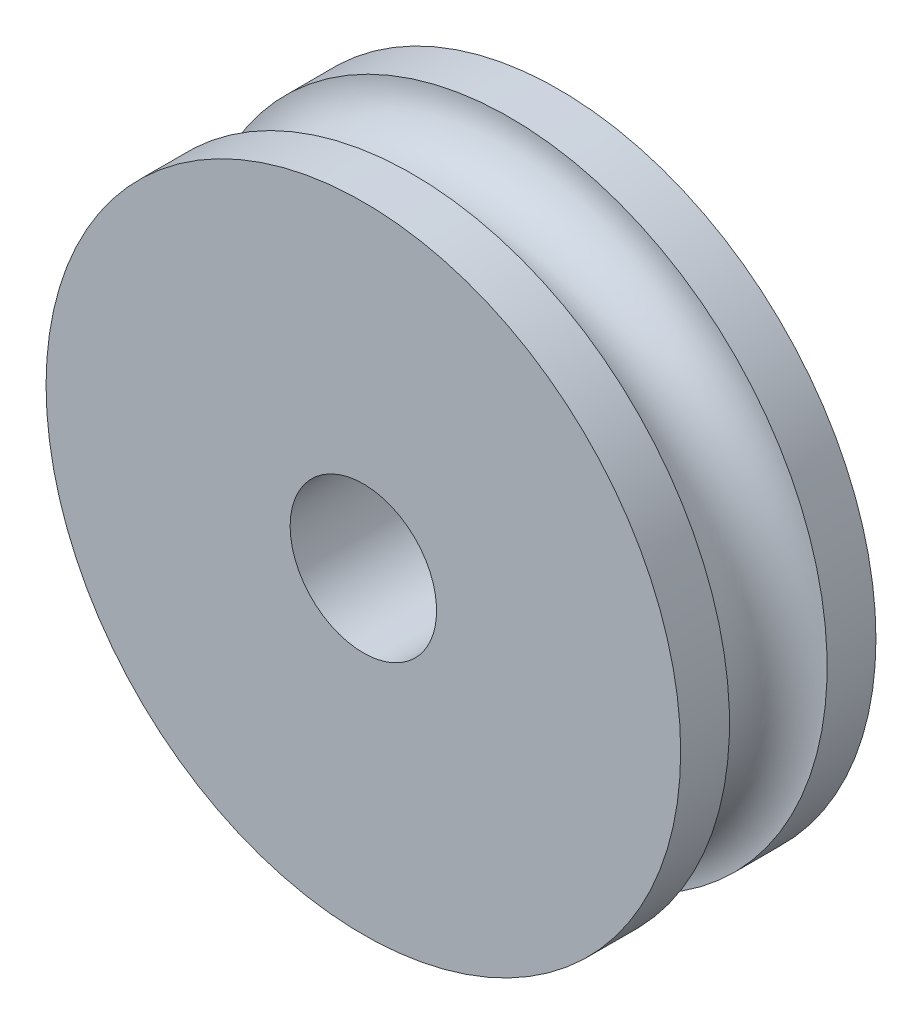
SolidWorks part; units mm, degrees
ref_plane "Front Plane" through (0, 0, 0) normal (0, 0, 1) x (1, 0, 0)
ref_plane "Top Plane" through (0, 0, 0) normal (0, 1, 0) x (1, 0, 0)
ref_plane "Right Plane" through (0, 0, 0) normal (1, 0, 0) x (0, 0, -1)
sketch "Sketch1" plane through (0, 0, 0) normal (0, 0, 1) x (1, 0, 0)
  circle A0 centre (0, 0) radius 6.5
  dimension "D1" = 13
extrude "Boss-Extrude1" add sketch "Sketch1" along normal blind 4
sketch "Sketch3" plane through (0, 0, 0) normal (0, 0, -1) x (-1, 0, 0)
  line L0 (0, 6.5) -> (0, -6.5)
  circle A0 centre (0, 0) radius 6.5 construction
ref_plane "Plane1" through (0, 0, 0) normal (1, 0, 0) x (0, -1, 0)
sketch "Sketch4" plane through (0, 0, 0) normal (1, 0, 0) x (0, -1, 0)
  line L2 (0, 0) -> (0, -4)
  line L4 (6.5, -4) -> (-6.5, -4) construction
  line L5 (-6.5, -4) -> (-6.5, 0) construction
  line L6 (-6.5, 0) -> (6.5, 0) construction
  line L7 (-6.5, 0) -> (6.5, 0) construction
  line L8 (6.5, 0) -> (6.5, -4) construction
  line L10 (6.5, -4) -> (6.5, 0) construction
  line L12 (6.5, -1) -> (6.5, -3)
  arc A1 (6.5, -1) -> (6.5, -3) centre (6.5, -2) ccw
  dimension "D1" = 1
revolve "Cut-Revolve1" cut sketch "Sketch4" angle 360 about L2
sketch "Sketch5" plane through (0, 0, 0) normal (0, 0, -1) x (-1, 0, 0)
  circle A0 centre (0, 0) radius 1.5
  dimension "D1" = 3
extrude "Cut-Extrude1" cut sketch "Sketch5" against normal blind 4
